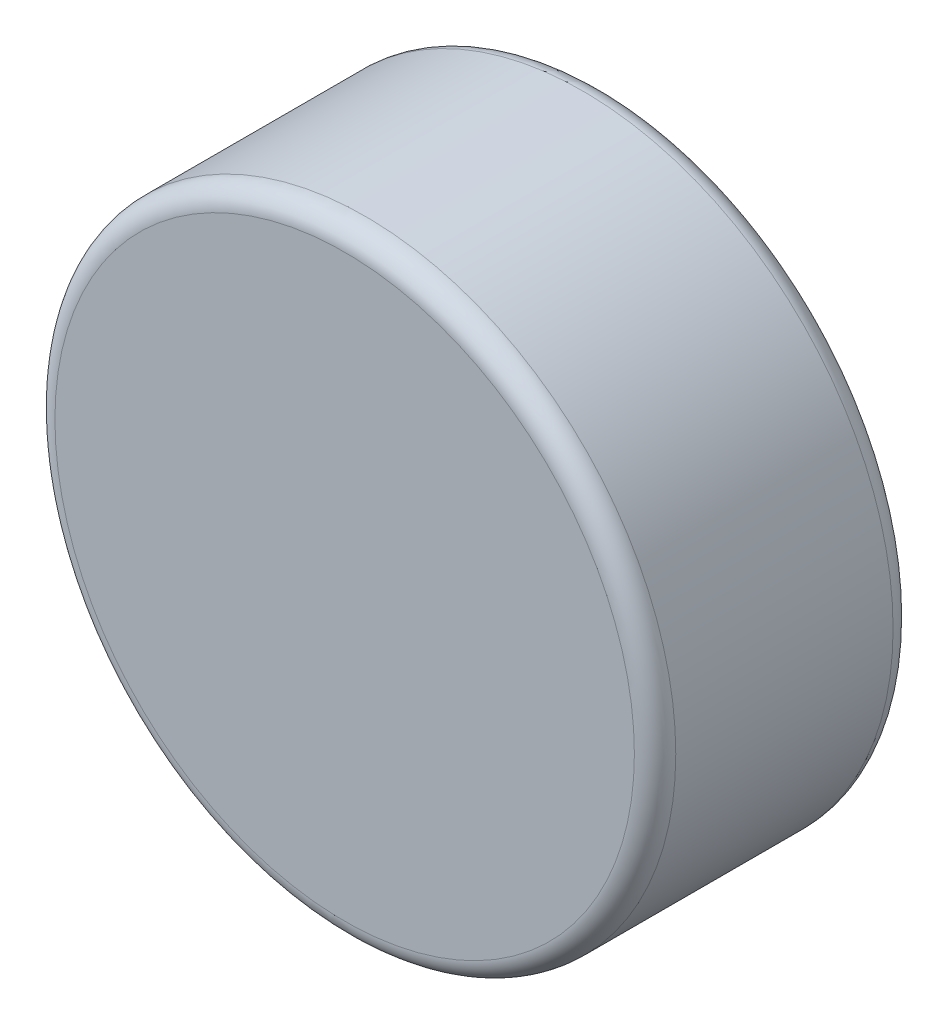
SolidWorks part; units mm, degrees
material "普通碳钢"
ref_plane "Front Plane" through (0, 0, 0) normal (0, 0, 1) x (1, 0, 0)
ref_plane "Top Plane" through (0, 0, 0) normal (0, 1, 0) x (1, 0, 0)
ref_plane "Right Plane" through (0, 0, 0) normal (1, 0, 0) x (0, 0, -1)
sketch "草图1" plane through (0, 0, 0) normal (0, 0, 1) x (1, 0, 0)
  circle A0 centre (0, 0) radius 3
  dimension "D1" = 6
extrude "凸台-拉伸2" add sketch "草图1" along normal blind 2.5
fillet "圆角2" radius 0.2 2 edges at (3, 0, 2.5) (3, 0, 0)
